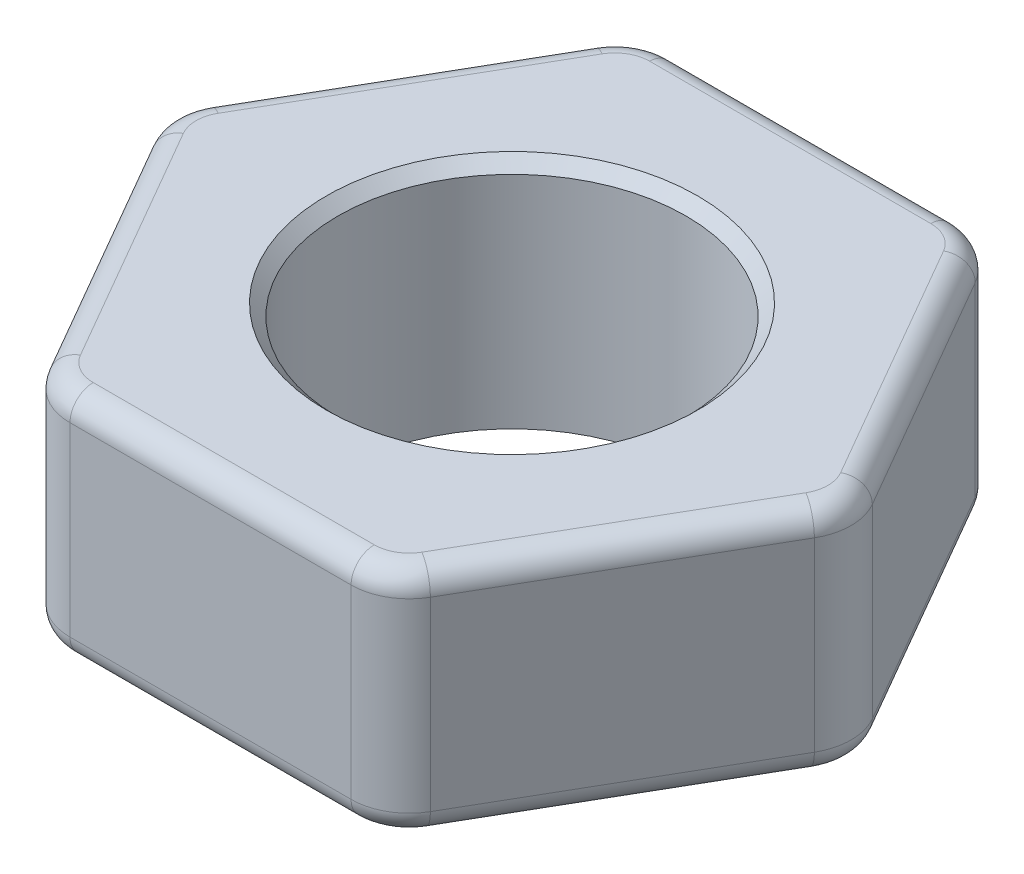
SolidWorks part; units mm, degrees
material "Plain Carbon Steel"
ref_plane "Front Plane" through (0, 0, 0) normal (0, 0, 1) x (1, 0, 0)
ref_plane "Top Plane" through (0, 0, 0) normal (0, 1, 0) x (1, 0, 0)
ref_plane "Right Plane" through (0, 0, 0) normal (1, 0, 0) x (0, 0, -1)
sketch "Sketch1" plane through (0, 0, 0) normal (0, 1, 0) x (1, 0, 0)
  line L1 (3, 0) -> (1.5, 2.5981)
  line L2 (1.5, 2.5981) -> (-1.5, 2.5981)
  line L3 (-1.5, 2.5981) -> (-3, 0)
  line L4 (-3, 0) -> (-1.5, -2.5981)
  line L5 (-1.5, -2.5981) -> (1.5, -2.5981)
  line L6 (1.5, -2.5981) -> (3, 0)
  circle A0 centre (0, 0) radius 2.5981 construction
  dimension "D1" = 6
  dimension "D2" = 5.1962
extrude "Boss-Extrude1" add sketch "Sketch1" along normal blind 2
sketch "Sketch2" plane through (0, 2, 0) normal (0, 1, 0) x (1, 0, 0)
  circle A0 centre (0, 0) radius 1.5
  dimension "D1" = 3
extrude "Cut-Extrude1" cut sketch "Sketch2" against normal through all
fillet "Fillet1" radius 0.5 6 edges at (-1.5, 1, 2.5981) (-3, 1, 0) (-1.5, 1, -2.5981) (1.5, 1, -2.5981) (3, 1, 0) (1.5, 1, 2.5981)
fillet "Fillet2" radius 0.2 24 edges at (-2.9226, 0, 0) (-2.25, 0, -1.299) (-1.4613, 0, -2.5311) (0, 0, -2.5981) (1.4613, 0, -2.5311) (2.25, 0, -1.299) (2.9226, 0, 0) (2.25, 0, 1.299) (1.4613, 0, 2.5311) (0, 0, 2.5981) (-1.4613, 0, 2.5311) (-1.4613, 2, -2.5311) (0, 2, -2.5981) (1.4613, 2, -2.5311) (2.25, 2, -1.299) (2.9226, 2, 0) (2.25, 2, 1.299) (1.4613, 2, 2.5311) (0, 2, 2.5981) (-1.4613, 2, 2.5311) (-2.25, 2, 1.299) (-2.9226, 2, 0) (-2.25, 0, 1.299) (-2.25, 2, -1.299)
chamfer "Chamfer1" distance 0.1 angle 45 1 edges at (0, 2, 1.5)
